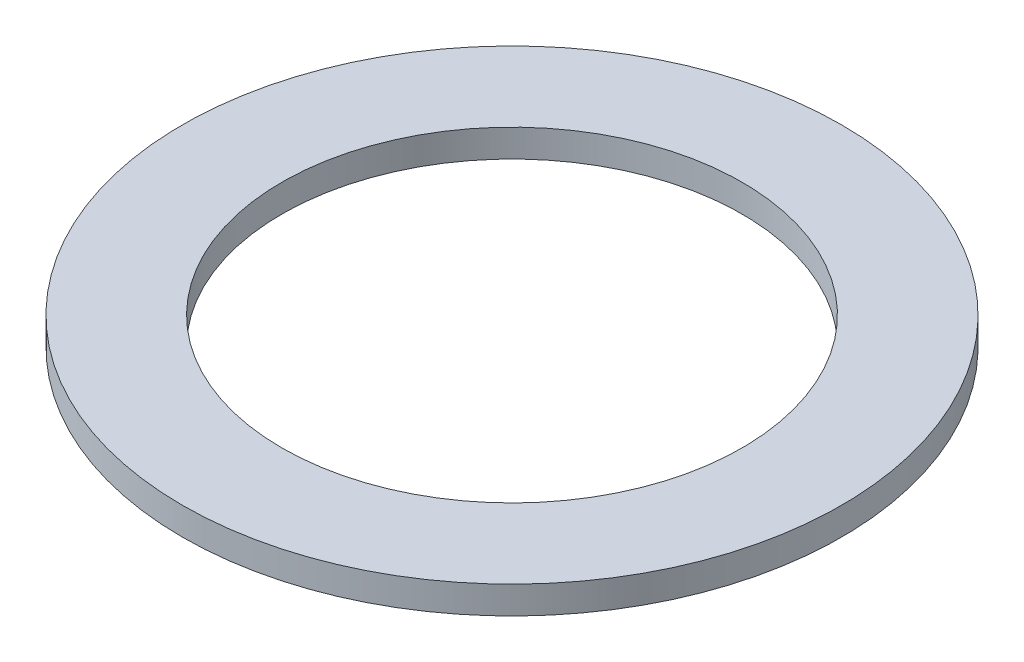
SolidWorks part; units mm, degrees
material "ABS"
ref_plane "前视基准面" through (0, 0, 0) normal (0, 0, 1) x (1, 0, 0)
ref_plane "上视基准面" through (0, 0, 0) normal (0, 1, 0) x (1, 0, 0)
ref_plane "右视基准面" through (0, 0, 0) normal (1, 0, 0) x (0, 0, -1)
sketch "草图1" plane through (0, 0, 0) normal (0, 1, 0) x (1, 0, 0)
  circle A0 centre (0, 0) radius 35.8
  circle A1 centre (0, 0) radius 20 construction
  circle A2 centre (0, -20) radius 2
  circle A3 centre (-17.3205, 10) radius 2
  circle A4 centre (17.3205, 10) radius 2
  circle A5 centre (0, 0) radius 7.5
  point P13 (0, 0)
  dimension "D1" = 71.6
  dimension "D2" = 40
  dimension "D3" = 4
  dimension "D5" = 15
  dimension "D4" = 3
extrude "凸台-拉伸1" add sketch "草图1" along normal blind 3
sketch "草图2" plane through (0, 3, 0) normal (0, 1, 0) x (1, 0, 0)
  circle A0 centre (0, 0) radius 25
  dimension "D1" = 50
extrude "切除-拉伸1" cut sketch "草图2" against normal blind 10
